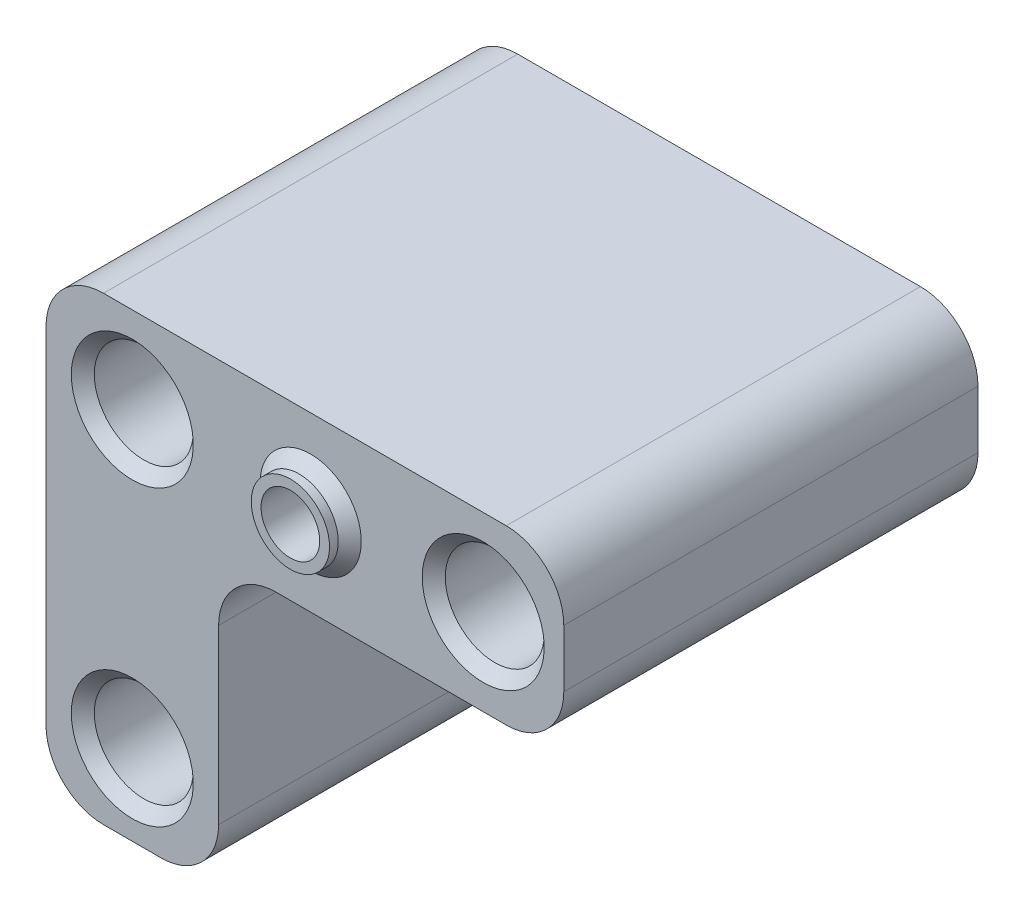
SolidWorks part; units mm, degrees
ref_plane "Front Plane" through (0, 0, 0) normal (0, 0, 1) x (1, 0, 0)
ref_plane "Top Plane" through (0, 0, 0) normal (0, 1, 0) x (1, 0, 0)
ref_plane "Right Plane" through (0, 0, 0) normal (1, 0, 0) x (0, 0, -1)
sketch "Sketch2" plane through (0, 0, 0) normal (0, 0, 1) x (1, 0, 0)
  line L1 (-311.5, 320) -> (-326.5, 320)
  line L2 (-311.5, 320) -> (-311.5, 360)
  line L3 (-311.5, 360) -> (-326.5, 360)
  line L4 (-326.5, 320) -> (-326.5, 360)
  line L5 (-311.5, 360) -> (-281.5, 360)
  line L6 (-311.5, 360) -> (-311.5, 345)
  line L7 (-311.5, 345) -> (-281.5, 345)
  line L8 (-281.5, 360) -> (-281.5, 345)
  line L10 (-281.5, 352.5) -> (-340.0828, 352.5) construction
  line L11 (-319, 320) -> (-319, 373.0529) construction
  line L12 (-303.5, 320) -> (-303.5, 373.0529) construction
  circle A0 centre (-319, 327) radius 2.55
  circle A1 centre (-288.5, 352.5) radius 2.55
  circle A2 centre (-319, 352.5) radius 2.55
  dimension "D7" = 5.1
  dimension "D8" = 5.1
  dimension "D11" = 0
  dimension "D13" = 5.1
  dimension "D1" = 15
  dimension "D2" = 15
  dimension "D4" = 30
  dimension "D5" = 40
  dimension "D9" = 7
  dimension "D10" = 7
  dimension "D12" = 0
extrude "Boss-Extrude1" add sketch "Sketch2" along normal blind 36 contours A1 | A2 | A0 | L2 L1 L4 L3 | L6 L7 L8 L5
sketch "Sketch3" plane through (0, 0, 36) normal (0, 0, 1) x (1, 0, 0)
  circle A0 centre (-319, 352.5) radius 4.3
  circle A1 centre (-319, 327) radius 4.3
  circle A2 centre (-288.5, 352.5) radius 4.3
  dimension "D1" = 8.6
extrude "Cut-Extrude1" cut sketch "Sketch3" against normal blind 30.6
sketch "Sketch4" plane through (0, 0, 0) normal (0, 0, -1) x (-1, 0, 0)
  line L0 (281.5, 352.5) -> (328.8705, 352.5)
  line L1 (281.5, 360) -> (281.5, 345) construction
  line L2 (311.5, 320) -> (311.5, 345) construction
  line L3 (307.55, 354.8383) -> (303.5, 357.1765)
  line L4 (303.5, 357.1765) -> (299.45, 354.8383)
  line L5 (299.45, 354.8383) -> (299.45, 350.1617)
  line L6 (299.45, 350.1617) -> (303.5, 347.8235)
  line L7 (303.5, 347.8235) -> (307.55, 350.1617)
  line L8 (307.55, 350.1617) -> (307.55, 354.8383)
  circle A0 centre (303.5, 352.5) radius 4.05
  circle A1 centre (288.5, 352.5) radius 2.55 construction
  circle A2 centre (303.5, 352.5) radius 4.05 construction
  dimension "D1" = 8.1
  dimension "D3" = 0
  dimension "D2" = 15
extrude "Cut-Extrude2" cut sketch "Sketch4" against normal blind 31.6 contours A0 | L5 L6 L7 L8 L3 L4
fillet "Fillet1" radius 5 6 edges at (-281.5, 360, 18) (-281.5, 345, 18) (-311.5, 345, 18) (-311.5, 320, 18) (-326.5, 320, 18) (-326.5, 360, 18)
chamfer "Chamfer1" distance 1 angle 45 3 edges at (-284.2, 352.5, 36) (-314.7, 352.5, 36) (-314.7, 327, 36)
sketch "Sketch8" plane through (0, 0, 31.6) normal (0, 0, -1) x (-1, 0, 0)
  line L0 (307.55, 350.1617) -> (299.45, 354.8383) construction
  line L2 (307.55, 354.8383) -> (299.45, 350.1617) construction
  circle A0 centre (303.5, 352.5) radius 2.55
  dimension "D1" = 5.1
extrude "Cut-Extrude3" cut sketch "Sketch8" against normal blind 10 contours A0
sketch "Sketch9" plane through (0, 0, 36) normal (0, 0, 1) x (1, 0, 0)
  circle A0 centre (-303.5, 352.5) radius 3.4
  circle A1 centre (-303.5, 352.5) radius 2.55
  dimension "D1" = 6.8
  dimension "D2" = 5.1
extrude "Boss-Extrude3" add sketch "Sketch9" along normal blind 1.76
chamfer "Chamfer3" distance 1 angle 45 1 edges at (-306.9, 352.5, 36)
chamfer "Chamfer4" distance 1 angle 45 6 edges at (-299.45, 352.5, 0) (-301.475, 348.9926, 0) (-305.525, 348.9926, 0) (-307.55, 352.5, 0) (-305.525, 356.0074, 0) (-301.475, 356.0074, 0)
